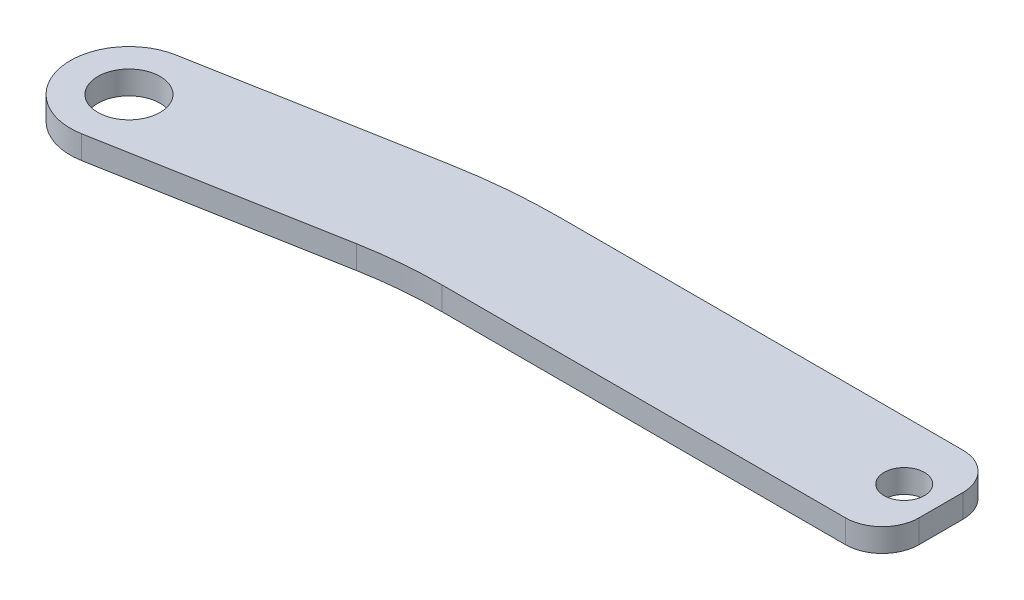
SolidWorks part; units mm, degrees
material "Copper"
ref_plane "Front Plane" through (0, 0, 0) normal (0, 0, 1) x (1, 0, 0)
ref_plane "Top Plane" through (0, 0, 0) normal (0, 1, 0) x (1, 0, 0)
ref_plane "Right Plane" through (0, 0, 0) normal (1, 0, 0) x (0, 0, -1)
sketch "Sketch1" plane through (0, 0, 0) normal (0, 1, 0) x (1, 0, 0)
  line L0 (-1.4287, 7.8714) -> (30.29, 13.6283)
  line L1 (43.8622, 14.85) -> (98.8622, 14.85)
  line L2 (98.8622, -1.15) -> (43.8622, -1.15)
  line L3 (33.1473, -2.1145) -> (1.4287, -7.8714)
  line L4 (103.8622, 3.85) -> (103.8622, 9.85)
  circle A0 centre (0, 0) radius 4.25
  circle A1 centre (98.8622, 6.85) radius 2.75
  arc A5 (1.4287, -7.8714) -> (-1.4287, 7.8714) centre (0, 0) cw
  arc A6 (43.8622, -1.15) -> (33.1473, -2.1145) centre (43.8622, -61.15) ccw
  arc A7 (43.8622, 14.85) -> (30.29, 13.6283) centre (43.8622, -61.15) ccw
  arc A9 (98.8622, -1.15) -> (103.8622, 3.85) centre (98.8622, 3.85) ccw
  arc A10 (103.8622, 9.85) -> (98.8622, 14.85) centre (98.8622, 9.85) ccw
  point P20 (0, 0)
  point P21 (103.7676, 4.0274)
  point P24 (103.8622, 6.85)
  dimension "D1" = 8.5
  dimension "D2" = 5.5
  dimension "D3" = 16
  dimension "D4" = 55
  dimension "D5" = 60
  dimension "D6" = 5
  dimension "D7" = 5
extrude "Boss-Extrude1" add sketch "Sketch1" along normal blind 3.175
